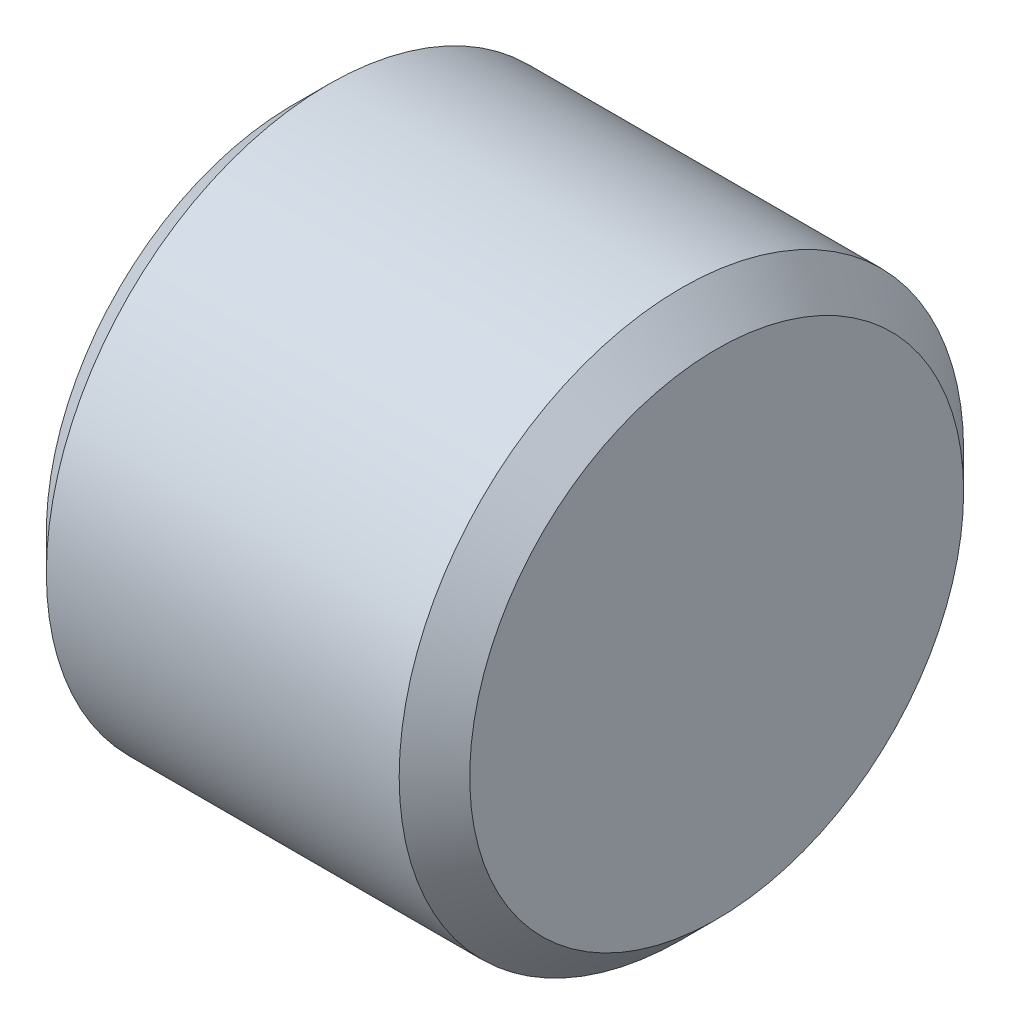
SolidWorks part; units mm, degrees
ref_plane "Front Plane" through (0, 0, 0) normal (0, 0, 1) x (1, 0, 0)
ref_plane "Top Plane" through (0, 0, 0) normal (0, 1, 0) x (1, 0, 0)
ref_plane "Right Plane" through (0, 0, 0) normal (1, 0, 0) x (0, 0, -1)
sketch "Sketch1" plane through (0, 0, 0) normal (1, 0, 0) x (0, 0, -1)
  circle A0 centre (0, 0) radius 4
extrude "Boss-Extrude1" add sketch "Sketch1" along normal blind 6
chamfer "Chamfer1" distance 0.5 angle 45 2 edges at (0, 0, -4) (6, 0, -4)
